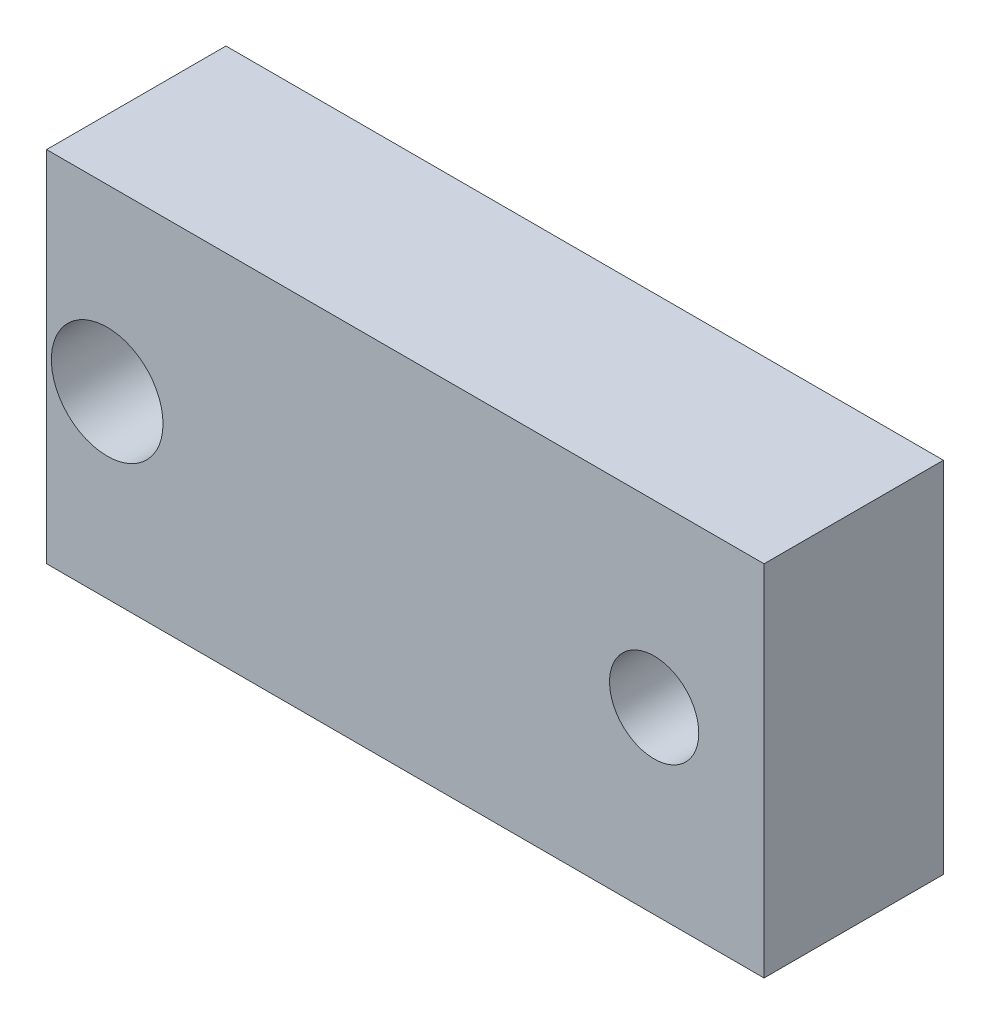
SolidWorks part; units mm, degrees
ref_plane "Front Plane" through (0, 0, 0) normal (0, 0, 1) x (1, 0, 0)
ref_plane "Top Plane" through (0, 0, 0) normal (0, 1, 0) x (1, 0, 0)
ref_plane "Right Plane" through (0, 0, 0) normal (1, 0, 0) x (0, 0, -1)
sketch "Sketch1" plane through (0, 0, 0) normal (0, 0, 1) x (1, 0, 0)
  line L1 (-12.7, -6.35) -> (12.7, -6.35)
  line L2 (-12.7, -6.35) -> (-12.7, 6.35)
  line L3 (-12.7, 6.35) -> (12.7, 6.35)
  line L4 (12.7, -6.35) -> (12.7, 6.35)
  line L5 (-12.7, -6.35) -> (12.7, 6.35) construction
  line L6 (-12.7, 6.35) -> (12.7, -6.35) construction
  circle A0 centre (-10.5552, 0) radius 1.9761
  circle A1 centre (8.8092, 0) radius 1.5793
  point P0 (0, 0)
  dimension "D1" = 12.7
  dimension "D2" = 25.4
extrude "Boss-Extrude1" add sketch "Sketch1" along normal blind 6.35
